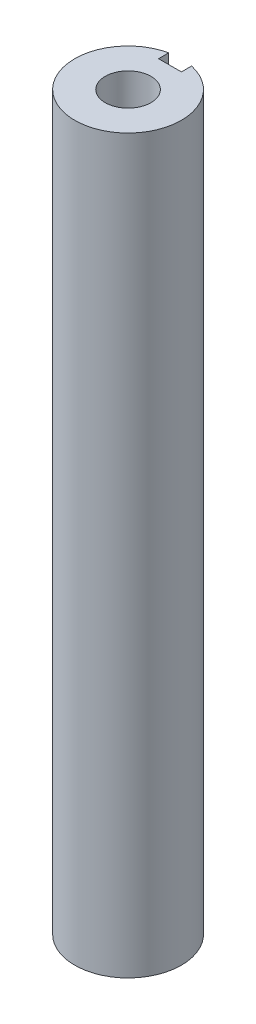
SolidWorks part; units mm, degrees
material "AISI 1045 Steel, cold drawn"
ref_plane "Front Plane" through (0, 0, 0) normal (0, 0, 1) x (1, 0, 0)
ref_plane "Top Plane" through (0, 0, 0) normal (0, 1, 0) x (1, 0, 0)
ref_plane "Right Plane" through (0, 0, 0) normal (1, 0, 0) x (0, 0, -1)
sketch "Sketch1" plane through (0, 0, 0) normal (0, 1, 0) x (1, 0, 0)
  line L0 (0, 0) -> (0, 74.8181) construction
  line L2 (-2.3813, 10.8544) -> (-2.3813, 8.7312)
  line L3 (-2.3813, 8.7312) -> (2.3813, 8.7312)
  line L4 (2.3813, 10.8544) -> (2.3813, 8.7312)
  line L5 (4.0598, 11.1125) -> (-6.0262, 11.1125) construction
  arc A1 (2.3813, 10.8544) -> (-2.3813, 10.8544) centre (0, 0) cw
  circle A2 centre (0, 0) radius 4.7625
  dimension "D1" = 6.35
  dimension "7/16" = 11.1125
  dimension "D2" = 4.7625
  dimension "D3" = 2.3813
extrude "Shaft" add sketch "Sketch1" along normal blind 152.4
sketch "Sketch3" plane through (0, 0, 0) normal (0, 0, 1) x (1, 0, 0)
  line L0 (0, 0) -> (0, 129.54)
  circle A0 centre (0, 129.54) radius 1.7859
  circle A1 centre (0, 129.54) radius 1.7859 construction
extrude "Cut-Extrude1" [suppressed] cut sketch "Sketch3" against normal through all both and the other way through all
chamfer "Chamfer1" [suppressed] distance 0.254 angle 45
